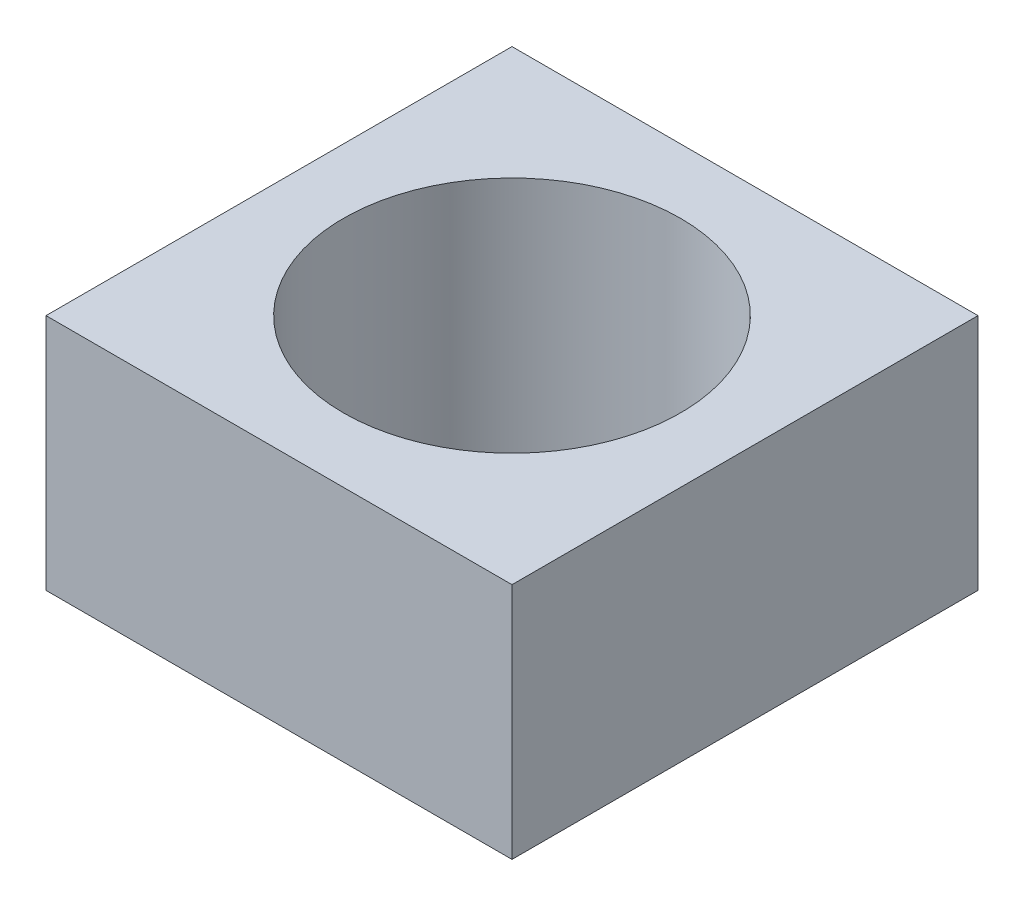
SolidWorks part; units mm, degrees
ref_plane "Front Plane" through (0, 0, 0) normal (0, 0, 1) x (1, 0, 0)
ref_plane "Top Plane" through (0, 0, 0) normal (0, 1, 0) x (1, 0, 0)
ref_plane "Right Plane" through (0, 0, 0) normal (1, 0, 0) x (0, 0, -1)
sketch "Sketch1" plane through (0, 0, 0) normal (0, 1, 0) x (1, 0, 0)
  line L1 (-37.3063, 37.3062) -> (37.3062, 37.3062)
  line L2 (-37.3063, 37.3062) -> (-37.3062, -37.3063)
  line L3 (-37.3062, -37.3063) -> (37.3063, -37.3063)
  line L4 (37.3062, 37.3062) -> (37.3063, -37.3063)
  line L5 (-37.3063, 37.3062) -> (37.3063, -37.3063) construction
  line L6 (-37.3062, -37.3063) -> (37.3062, 37.3062) construction
  point P0 (0, 0)
  dimension "D1" = 74.6125
  dimension "D2" = 74.6125
extrude "Boss-Extrude1" add sketch "Sketch1" along normal blind 38.1
sketch "Sketch2" plane through (0, 38.1, 0) normal (0, 1, 0) x (1, 0, 0)
  circle A0 centre (0, 0) radius 26.9875
extrude "Cut-Extrude1" cut sketch "Sketch2" against normal through all
